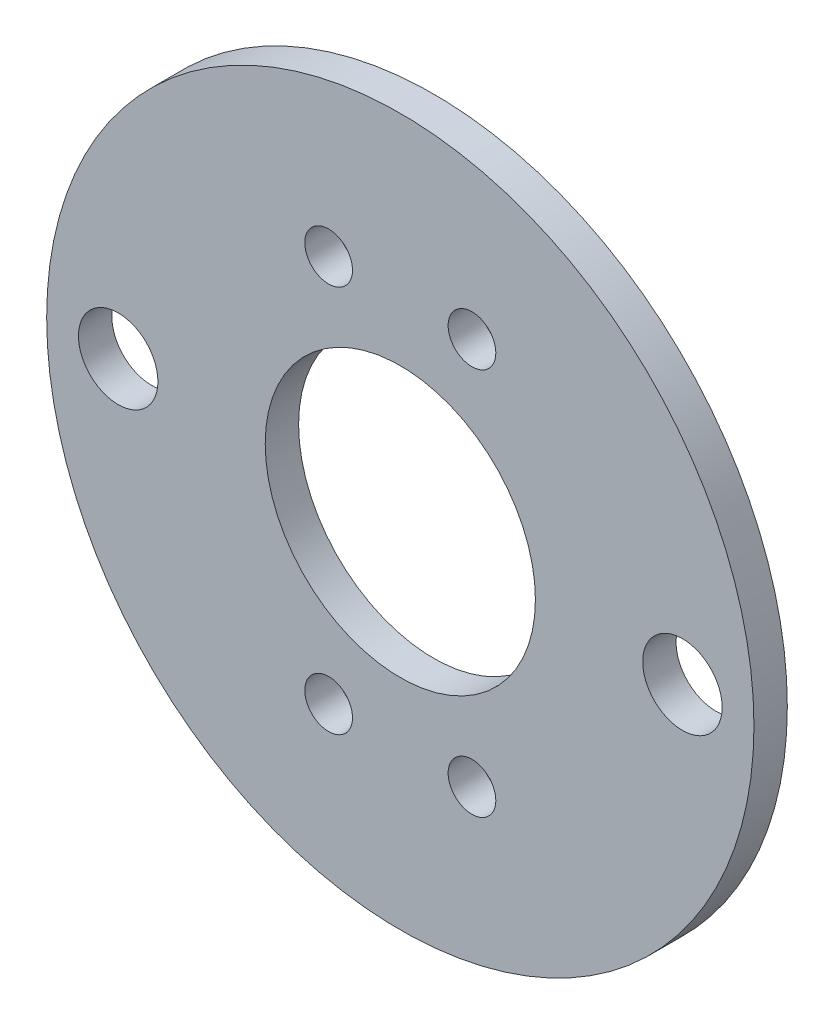
SolidWorks part; units mm, degrees
ref_plane "Front Plane" through (0, 0, 0) normal (0, 0, 1) x (1, 0, 0)
ref_plane "Top Plane" through (0, 0, 0) normal (0, 1, 0) x (1, 0, 0)
ref_plane "Right Plane" through (0, 0, 0) normal (1, 0, 0) x (0, 0, -1)
sketch "Sketch1" plane through (0, 0, 0) normal (0, 0, 1) x (1, 0, 0)
  line L1 (0, 0) -> (15.25, 0) construction
  line L2 (15.25, 0) -> (20.25, 0) construction
  line L3 (20.25, 0) -> (22.25, 0) construction
  circle A2 centre (0, 0) radius 22.25
  circle A11 centre (0, 0) radius 8.5
  circle A13 centre (17.75, 0) radius 2.5
  circle A21 centre (-17.75, 0) radius 2.5
  circle A22 centre (0, 0) radius 9.5 construction
  circle A25 centre (0, 0) radius 9.5 construction
  point P7 (0, 0)
  point P11 (0, 0)
  point P13 (0, 0)
  point P20 (0, 0)
  point P34 (0, 0)
  dimension "D1" = 1
  dimension "D2" = 2
  dimension "D4" = 44.5
  dimension "D3" = 5
extrude "Boss-Extrude1" add sketch "Sketch1" along normal blind 2.1
sketch "Sketch3" plane through (0, 0, 0) normal (0, 0, 1) x (1, 0, 0)
  line L0 (-22.25, 0) -> (22.25, 0) construction
  line L1 (0, -22.25) -> (0, 22.25) construction
  circle A0 centre (17.75, 0) radius 12.5 construction
  circle A1 centre (17.75, 0) radius 12.5 construction
  circle A2 centre (-17.75, 0) radius 12.5 construction
  circle A3 centre (-17.75, 0) radius 12.5 construction
  circle A4 centre (17.75, 0) radius 13.5 construction
  circle A5 centre (4.5088, -12.1931) radius 4.5 construction
  circle A6 centre (0, 0) radius 8.5 construction
  circle A7 centre (4.5088, -12.1931) radius 1.5
  circle A8 centre (0, 0) radius 22.25 construction
  circle A9 centre (4.5088, 12.1931) radius 1.5
  circle A10 centre (-4.5088, -12.1931) radius 1.5
  circle A11 centre (-4.5088, 12.1931) radius 1.5
  point P17 (0, 0)
  point P23 (0, 0)
  dimension "D1" = 1
  dimension "D2" = 9
  dimension "D3" = 3
extrude "Cut-Extrude2" cut sketch "Sketch3" against normal through all and the other way through all
